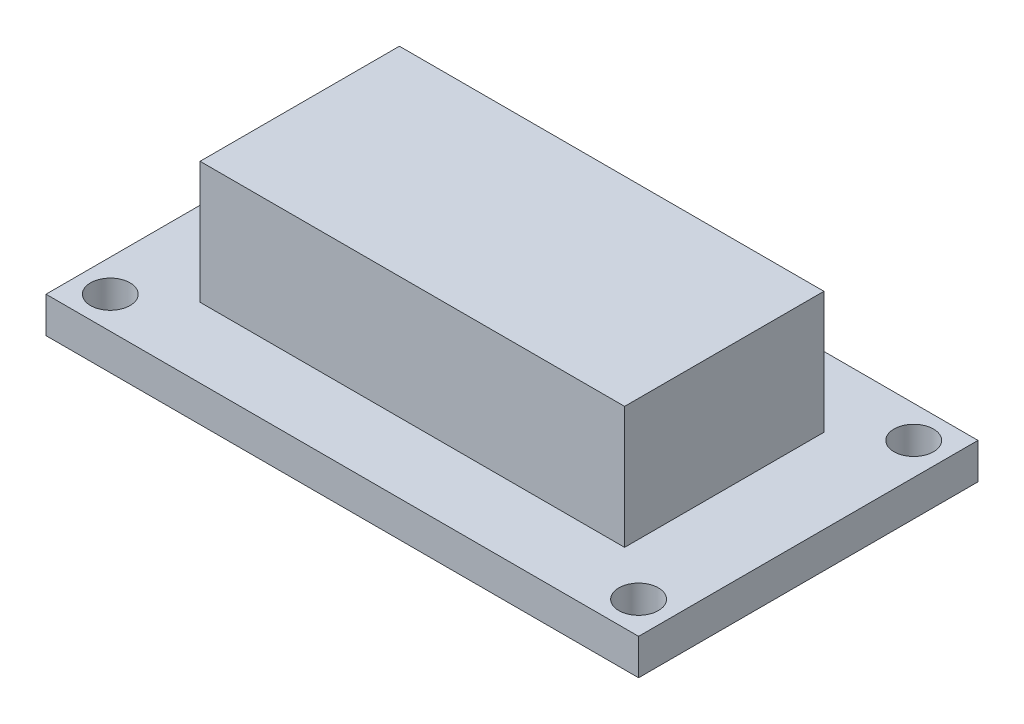
SolidWorks part; units mm, degrees
ref_plane "Front" through (0, 0, 0) normal (0, 0, 1) x (1, 0, 0)
ref_plane "Top" through (0, 0, 0) normal (0, 1, 0) x (1, 0, 0)
ref_plane "Right" through (0, 0, 0) normal (1, 0, 0) x (0, 0, -1)
sketch "Sketch1" plane through (0, 0, 0) normal (0, 1, 0) x (1, 0, 0)
  line L1 (-20.955, 12.0015) -> (20.955, 12.0015)
  line L2 (-20.955, 12.0015) -> (-20.955, -12.0015)
  line L3 (-20.955, -12.0015) -> (20.955, -12.0015)
  line L4 (20.955, 12.0015) -> (20.955, -12.0015)
  line L5 (-20.955, 12.0015) -> (20.955, -12.0015) construction
  line L6 (-20.955, -12.0015) -> (20.955, 12.0015) construction
  line L7 (-55, 0) -> (55, 0) construction
  line L8 (0, -55) -> (0, 55) construction
  circle A0 centre (-18.6817, 9.7282) radius 1.397
  circle A1 centre (-18.6817, -9.7282) radius 1.397
  circle A2 centre (18.6817, -9.7282) radius 1.397
  circle A3 centre (18.6817, 9.7282) radius 1.397
  point P0 (0, 0)
  dimension "D3" = 2.794
  dimension "D1" = 41.91
  dimension "D2" = 24.003
  dimension "D4" = 2.2733
  dimension "D5" = 2.2733
extrude "Boss-Extrude1" add sketch "Sketch1" along normal blind 2.54 contours L2 L3 L4 L1 | A0 | A3 | A2 | A1
sketch "Sketch2" plane through (0, 2.54, 0) normal (0, 1, 0) x (1, 0, 0)
  line L1 (-15.0114, 7.0485) -> (15.0114, 7.0485)
  line L2 (-15.0114, 7.0485) -> (-15.0114, -7.0485)
  line L3 (-15.0114, -7.0485) -> (15.0114, -7.0485)
  line L4 (15.0114, 7.0485) -> (15.0114, -7.0485)
  line L5 (-15.0114, 7.0485) -> (15.0114, -7.0485) construction
  line L6 (-15.0114, -7.0485) -> (15.0114, 7.0485) construction
  point P0 (0, 0)
  dimension "D1" = 30.0228
  dimension "D2" = 14.097
extrude "Boss-Extrude2" add sketch "Sketch2" along normal blind 8.636
